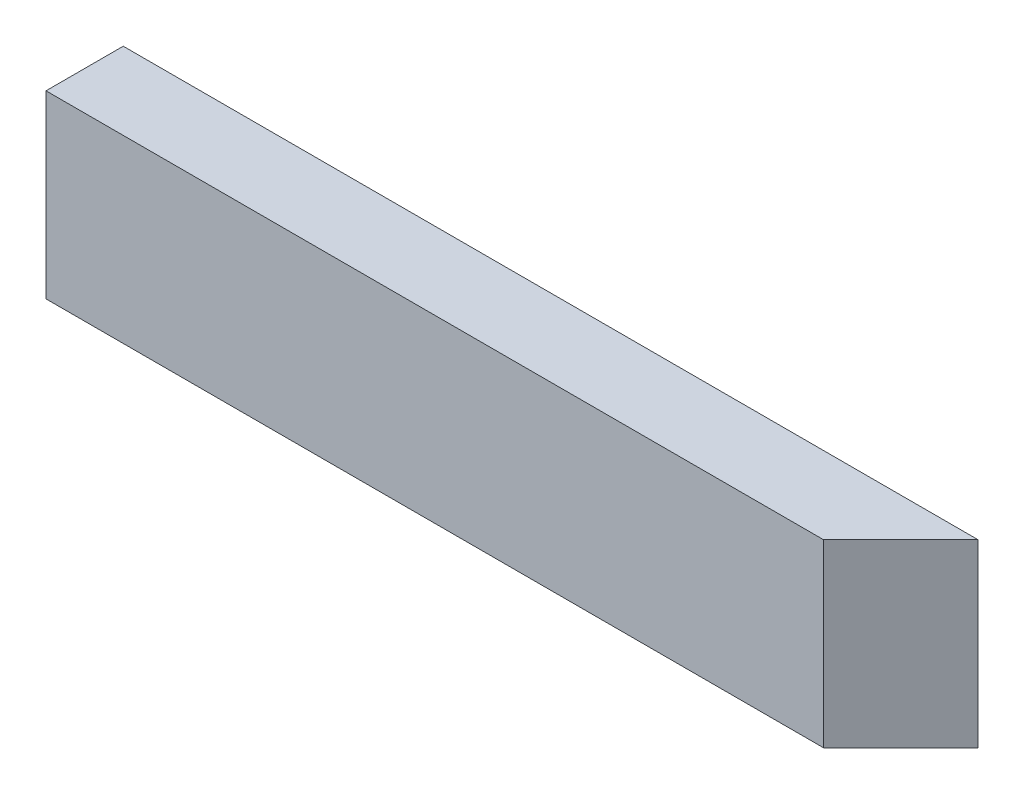
SolidWorks part; units mm, degrees
ref_plane "Front Plane" through (0, 0, 0) normal (0, 0, 1) x (1, 0, 0)
ref_plane "Top Plane" through (0, 0, 0) normal (0, 1, 0) x (1, 0, 0)
ref_plane "Right Plane" through (0, 0, 0) normal (1, 0, 0) x (0, 0, -1)
sketch "Sketch1" plane through (0, 0, 0) normal (0, 1, 0) x (1, 0, 0)
  line L0 (421.64, 38.1) -> (383.54, 0)
  line L1 (0, 0) -> (383.54, 0)
  line L2 (0, 0) -> (0, 38.1)
  line L3 (0, 38.1) -> (421.64, 38.1)
  dimension "D1" = 38.1
  dimension "D2" = 421.64
extrude "Boss-Extrude2" add sketch "Sketch1" along normal blind 88.9
